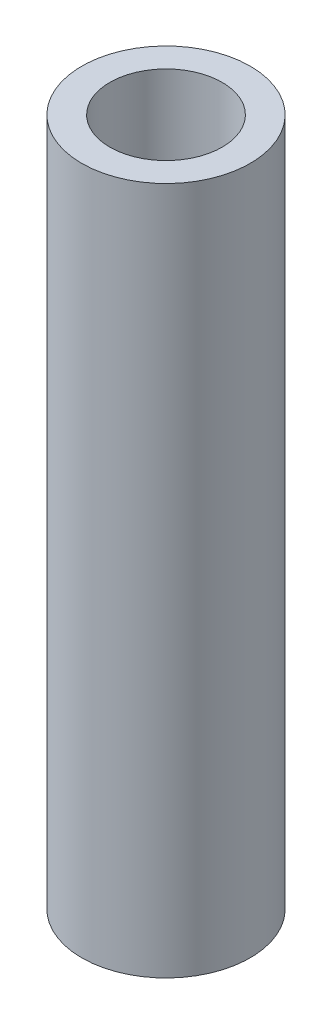
SolidWorks part; units mm, degrees
ref_plane "Plan de face" through (0, 0, 0) normal (0, 0, 1) x (1, 0, 0)
ref_plane "Plan de dessus" through (0, 0, 0) normal (0, 1, 0) x (1, 0, 0)
ref_plane "Plan de droite" through (0, 0, 0) normal (1, 0, 0) x (0, 0, -1)
sketch "Esquisse1" plane through (0, 0, 0) normal (0, 1, 0) x (1, 0, 0)
  circle A0 centre (-29.6521, -2.6385) radius 2
  circle A1 centre (-29.6521, -2.6385) radius 3
  dimension "D1" = 4
  dimension "D2" = 6
extrude "Boss.-Extru.1" add sketch "Esquisse1" along normal blind 24.5
